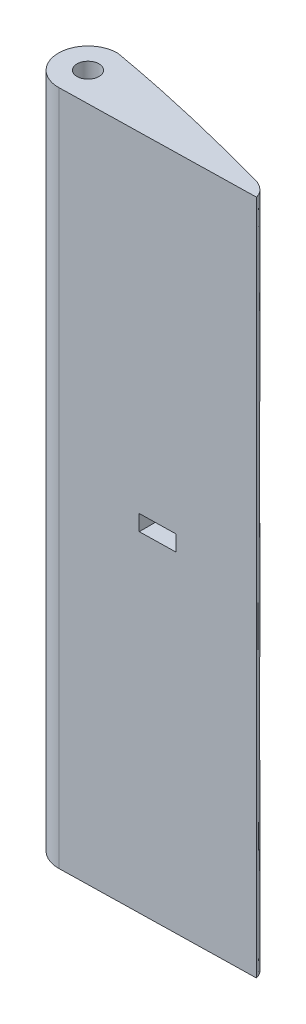
SolidWorks part; units mm, degrees
ref_plane "Front Plane" through (0, 0, 0) normal (0, 0, 1) x (1, 0, 0)
ref_plane "Top Plane" through (0, 0, 0) normal (0, 1, 0) x (1, 0, 0)
ref_plane "Right Plane" through (0, 0, 0) normal (1, 0, 0) x (0, 0, -1)
sketch "Sketch1" plane through (0, 0, 0) normal (0, 1, 0) x (1, 0, 0)
  line L3 (94.9027, -1.5399) -> (126.1537, -0.9051)
  circle A1 centre (94.8054, 3.25) radius 1.778
  arc A2 (94.8054, 8.0408) -> (94.9027, -1.5399) centre (94.8054, 3.25) ccw
  spline S1 degree 3 poles (94.8054, 8.0408) (104.7257, 6.2845) (114.5405, 3.9599) (124.2333, 1.2207) knots 0 0 0 0 1 1 1 1
  spline S2 degree 3 poles (124.2333, 1.2207) (125.0838, 0.7937) (125.9655, 0.0882) (126.1537, -0.9051) knots 0 0 0 0 1 1 1 1
  dimension "D1" = 3.556
extrude "Boss-Extrude1" add sketch "Sketch1" along normal blind 109.22
ref_plane "Plane1" through (0, 0, 2.54) normal (0, 0, 1) x (1, 0, 0)
sketch "Sketch3" plane through (0, 0, 2.54) normal (0, 0, 1) x (1, 0, 0)
  line L0 (90.0145, 54.61) -> (126.1537, 54.61)
  line L1 (90.0145, 109.22) -> (90.0145, 0) construction
  line L2 (126.1537, 109.22) -> (126.1537, 0) construction
  line L3 (110.5282, 109.22) -> (110.5282, 0)
  line L4 (94.9027, 109.22) -> (126.1537, 109.22) construction
  line L5 (94.9027, 0) -> (126.1537, 0) construction
  line L7 (113.4492, 53.34) -> (107.6072, 53.34)
  line L8 (113.4492, 53.34) -> (113.4492, 55.88)
  line L9 (113.4492, 55.88) -> (107.6072, 55.88)
  line L10 (107.6072, 53.34) -> (107.6072, 55.88)
  line L11 (113.4492, 53.34) -> (107.6072, 55.88) construction
  line L12 (113.4492, 55.88) -> (107.6072, 53.34) construction
  point P12 (110.5282, 54.61)
  dimension "D1" = 2.54
  dimension "D2" = 5.842
extrude "Cut-Extrude1" cut sketch "Sketch3" against normal blind 5.842 contours L10 L0 L3 L9 | L8 L9 L3 L0 | L10 L7 L3 L0 | L7 L8 L0 L3
